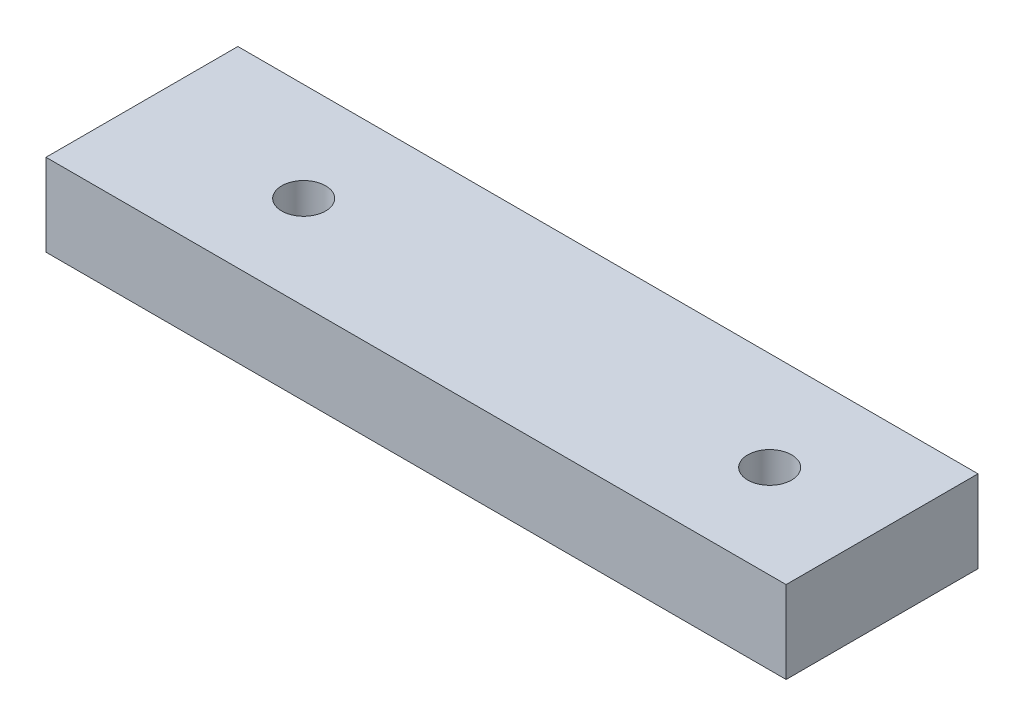
SolidWorks part; units mm, degrees
ref_plane "Front Plane" through (0, 0, 0) normal (0, 0, 1) x (1, 0, 0)
ref_plane "Top Plane" through (0, 0, 0) normal (0, 1, 0) x (1, 0, 0)
ref_plane "Right Plane" through (0, 0, 0) normal (1, 0, 0) x (0, 0, -1)
sketch "Sketch6" plane through (0, 0, 0) normal (0, 0, 1) x (1, 0, 0)
  line L1 (0, 0) -> (135, 0)
  line L2 (0, 0) -> (0, 15)
  line L3 (0, 15) -> (135, 15)
  line L4 (135, 0) -> (135, 15)
  dimension "D1" = 135
  dimension "D2" = 15
extrude "Boss-Extrude1" add sketch "Sketch6" along normal blind 35
sketch "Sketch7" plane through (0, 15, 0) normal (0, 1, 0) x (1, 0, 0)
  line L0 (0, -35) -> (0, 0) construction
  line L2 (135, 0) -> (0, 0) construction
  circle A0 centre (30, -18) radius 4
  circle A1 centre (115, -18) radius 4
  dimension "D1" = 8
  dimension "D2" = 8
  dimension "D3" = 30
  dimension "D4" = 18
  dimension "D5" = 18
  dimension "D6" = 85
extrude "Cut-Extrude1" cut sketch "Sketch7" against normal blind 50
